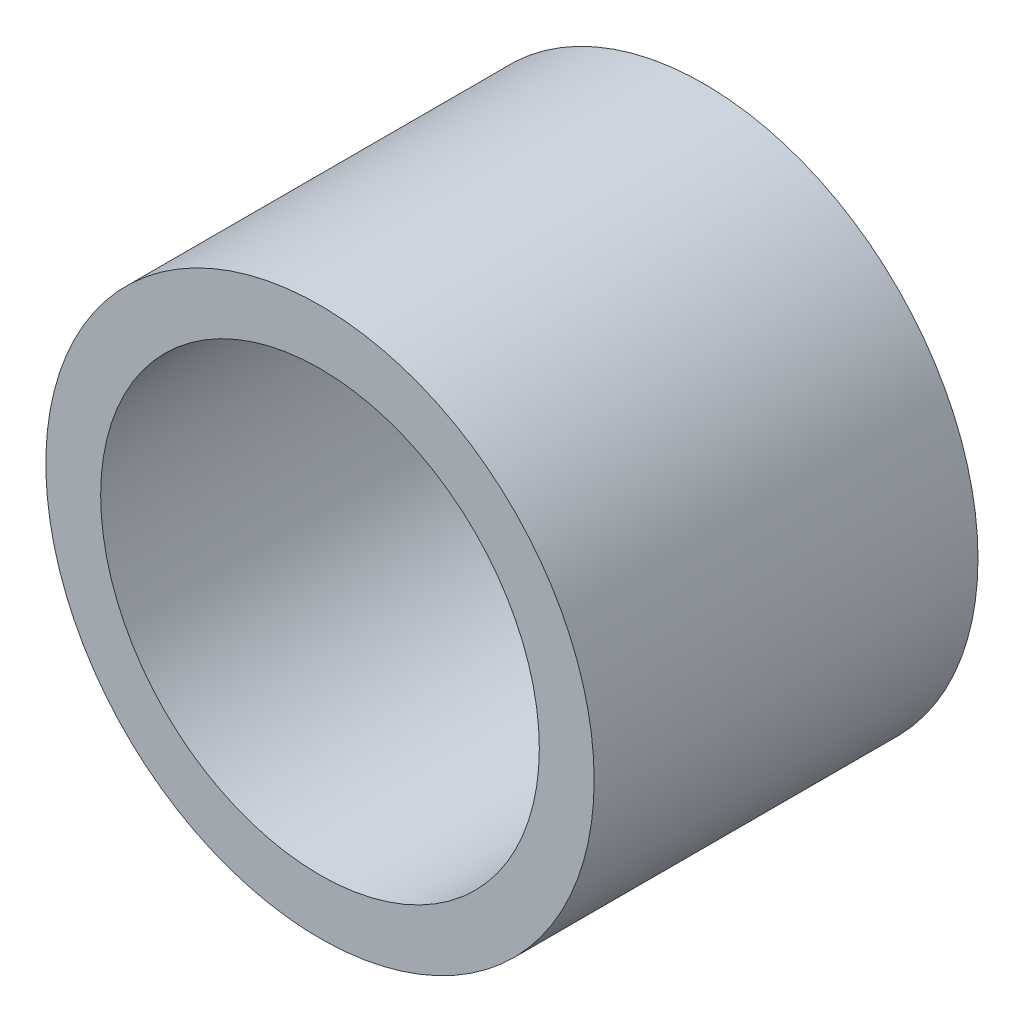
SolidWorks part; units mm, degrees
ref_plane "Alzado" through (0, 0, 0) normal (0, 0, 1) x (1, 0, 0)
ref_plane "Planta" through (0, 0, 0) normal (0, 1, 0) x (1, 0, 0)
ref_plane "Vista lateral" through (0, 0, 0) normal (1, 0, 0) x (0, 0, -1)
sketch "Croquis1" plane through (0, 0, 0) normal (0, 0, 1) x (1, 0, 0)
  circle A0 centre (0, 0) radius 5
  circle A1 centre (0, 0) radius 4
  dimension "D1" = 10
  dimension "D2" = 8
extrude "Saliente-Extruir1" add sketch "Croquis1" along normal blind 7
